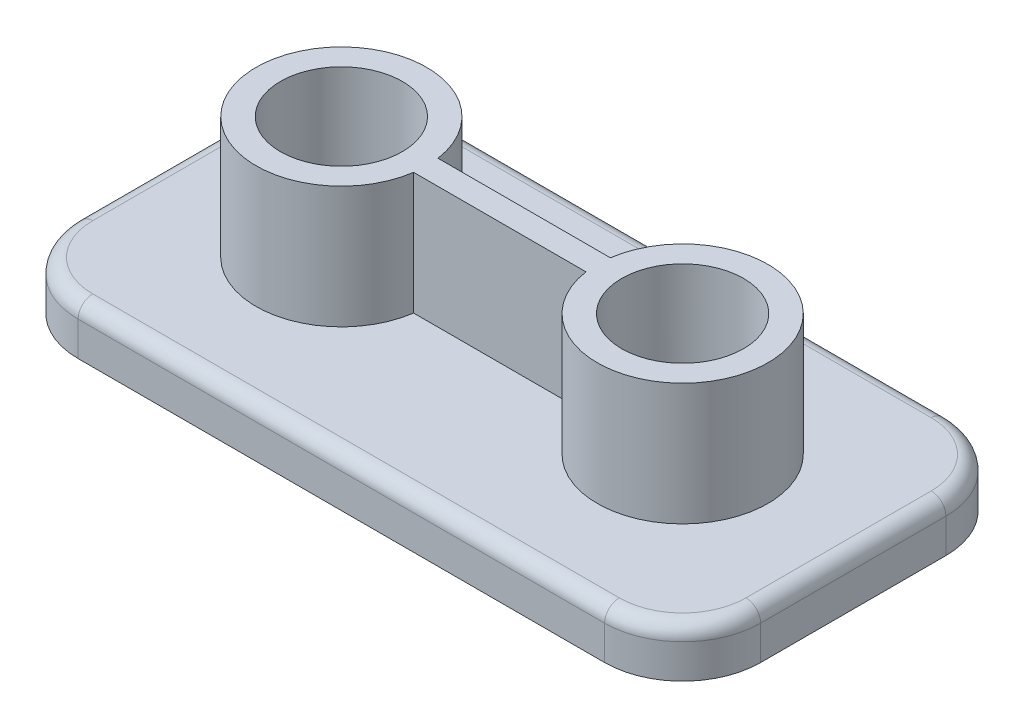
SolidWorks part; units mm, degrees
material "AISI 304"
ref_plane "정면" through (0, 0, 0) normal (0, 0, 1) x (1, 0, 0)
ref_plane "윗면" through (0, 0, 0) normal (0, 1, 0) x (1, 0, 0)
ref_plane "우측면" through (0, 0, 0) normal (1, 0, 0) x (0, 0, -1)
sketch "Sketch1" plane through (0, 0, 0) normal (0, 1, 0) x (1, 0, 0)
  line L1 (0, 0) -> (140, 0)
  line L2 (0, 0) -> (0, 70)
  line L3 (0, 70) -> (140, 70)
  line L4 (140, 0) -> (140, 70)
  dimension "D1" = 140
  dimension "D2" = 70
extrude "Boss-Extrude1" add sketch "Sketch1" along normal blind 10
sketch "Sketch2" plane through (0, 10, 0) normal (0, 1, 0) x (1, 0, 0)
  line L0 (70, 70) -> (70, 0) construction
  line L1 (140, 70) -> (0, 70) construction
  line L2 (0, 0) -> (140, 0) construction
  line L4 (105, 37.5) -> (35, 37.5)
  line L5 (105, 32.5) -> (35, 32.5)
  line L6 (105, 37.5) -> (105, 32.5)
  line L7 (35, 37.5) -> (35, 32.5)
  circle A0 centre (35, 35) radius 12.5
  circle A1 centre (105, 35) radius 12.5
  circle A2 centre (35, 35) radius 17.5
  circle A3 centre (105, 35) radius 17.5
  point P10 (70, 35)
  point P17 (0, 0)
  point P18 (0, 0)
  point P19 (0, 0)
  dimension "D2" = 25
  dimension "D3" = 35
  dimension "D6" = 35
  dimension "D1" = 70
  dimension "D4" = 5
extrude "Boss-Extrude2" add sketch "Sketch2" along normal blind 25 contours L4 A2 L5 A0 | L5 A2 L4 A0 | L0 L4 A2 L5 | L4 L0 L5 A3 | L4 A3 L5 A1 | L5 A3 L4 A1
fillet "Fillet2" radius 16 4 edges at (0, 5, -70) (140, 5, -70) (140, 5, 0) (0, 5, 0)
fillet "Fillet1" radius 3 8 edges at (70, 10, -70) (140, 10, -35) (70, 10, 0) (0, 10, -35) (4.6863, 10, -65.3137) (135.3137, 10, -65.3137) (135.3137, 10, -4.6863) (4.6863, 10, -4.6863)
